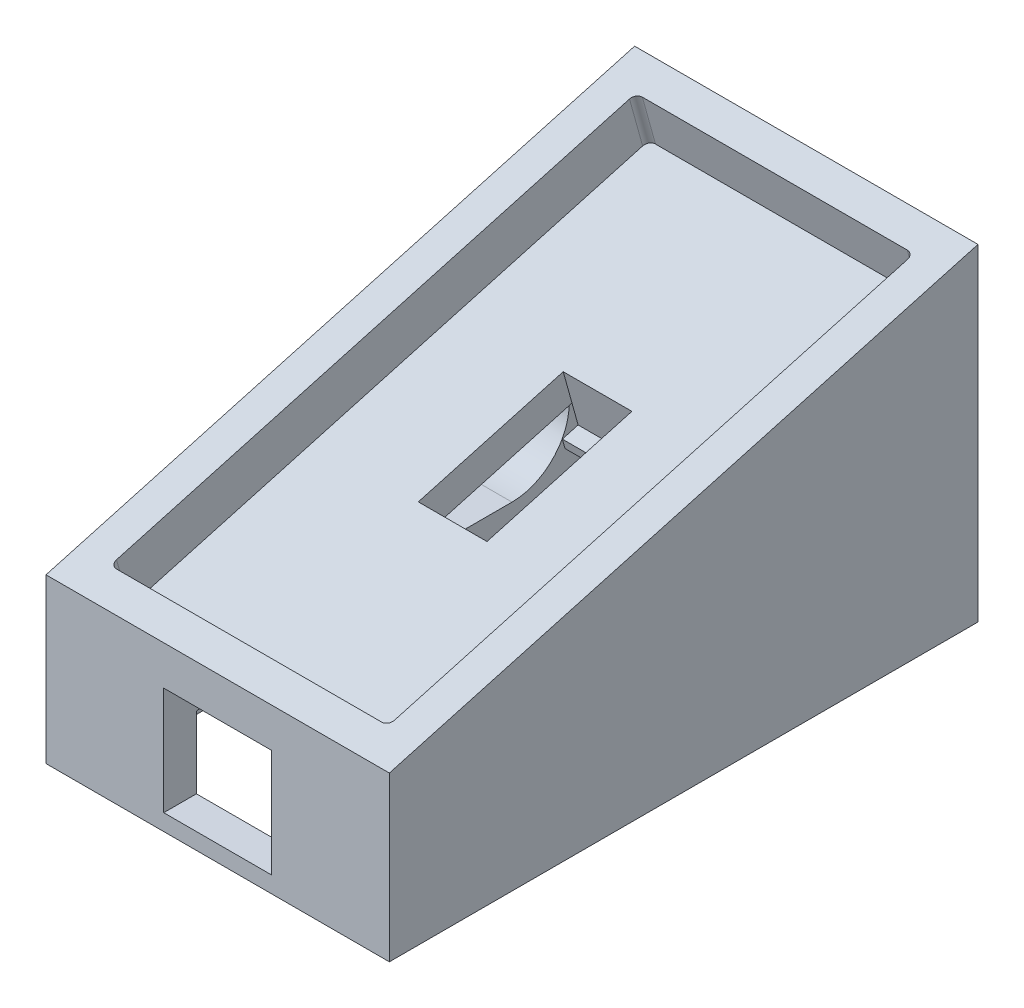
SolidWorks part; units mm, degrees
ref_plane "Front Plane" through (0, 0, 0) normal (0, 0, 1) x (1, 0, 0)
ref_plane "Top Plane" through (0, 0, 0) normal (0, 1, 0) x (1, 0, 0)
ref_plane "Right Plane" through (0, 0, 0) normal (1, 0, 0) x (0, 0, -1)
sketch "Sketch2" plane through (0, 0, 0) normal (0, 1, 0) x (1, 0, 0)
  line L0 (0, 0) -> (300, 0)
  line L1 (300, 0) -> (300, 180)
  line L2 (300, 180) -> (0, 180)
  line L3 (0, 180) -> (0, 0)
  line L4 (300, 0) -> (174.5704, 0)
  dimension "D1" = 180
  dimension "D2" = 300
extrude "Boss-Extrude1" add sketch "Sketch2" along normal blind 50 contours L3 L0 L1 L2
sketch "Sketch3" plane through (0, 50, 0) normal (0, 1, 0) x (1, 0, 0)
  line L0 (0, 0) -> (5, 0)
  line L1 (0, 0) -> (300, 0) construction
  line L2 (90, 12) -> (90, 73)
  line L5 (0, 180) -> (0, 0) construction
  line L13 (12, 10) -> (78, 10)
  line L14 (10, 12) -> (10, 73)
  line L15 (12, 75) -> (78, 75)
  line L16 (80, 12) -> (80, 73)
  line L22 (10, 10) -> (80, 10)
  line L26 (92, 10) -> (183, 10)
  line L27 (90, 10) -> (90, 75)
  line L28 (92, 75) -> (183, 75)
  line L29 (185, 12) -> (185, 73)
  line L30 (180, 70) -> (180, 75)
  line L32 (90, 10) -> (185, 10)
  line L34 (10, 75) -> (10, 10)
  line L35 (90, 10) -> (90, 75) construction
  line L37 (80, 10) -> (80, 75) construction
  arc A0 (90, 12) -> (92, 10) centre (92, 12) ccw
  arc A1 (185, 12) -> (183, 10) centre (183, 12) cw
  arc A2 (183, 75) -> (185, 73) centre (183, 73) cw
  arc A3 (80, 73) -> (78, 75) centre (78, 73) ccw
  arc A4 (12, 10) -> (10, 12) centre (12, 12) cw
  arc A5 (80, 12) -> (78, 10) centre (78, 12) cw
  arc A6 (10, 73) -> (12, 75) centre (12, 73) cw
  arc A7 (92, 75) -> (90, 73) centre (92, 73) ccw
  point P32 (80, 75)
  dimension "D7" = 2
  dimension "D4" = 2
  dimension "D1" = 10
  dimension "D3" = 65
  dimension "D5" = 70
  dimension "D8" = 95
  dimension "D9" = 65
  dimension "D2" = 10
  dimension "D11" = 10
extrude "Cut-Extrude1" cut sketch "Sketch3" against normal blind 15 contours L13 L16 L15 L14 | L26 L29 L28 L2
sketch "Sketch6" plane through (0, 50, 0) normal (0, 1, 0) x (1, 0, 0)
  line L2 (185, 12) -> (185, 73) construction
  line L4 (0, 180) -> (185, 180)
  line L14 (0, 180) -> (0, 95)
  line L15 (0, 95) -> (185, 95)
  line L16 (185, 168) -> (185, 107)
  line L17 (80, 107) -> (80, 168)
  line L23 (90, 107) -> (90, 168)
  line L25 (12, 170) -> (78, 170)
  line L26 (10, 168) -> (10, 107)
  line L27 (12, 105) -> (78, 105)
  line L32 (195, 180) -> (195, 95)
  line L34 (185, 180) -> (195, 180)
  line L35 (195, 95) -> (185, 95)
  line L37 (92, 105) -> (183, 105)
  line L44 (0, 105) -> (185, 105) construction
  line L45 (92, 170) -> (183, 170)
  line L46 (0, 170) -> (185, 170) construction
  line L47 (10, 180) -> (10, 95) construction
  line L48 (185, 180) -> (185, 95) construction
  arc A0 (185, 107) -> (183, 105) centre (183, 107) cw
  arc A1 (185, 168) -> (183, 170) centre (183, 168) ccw
  arc A2 (90, 168) -> (92, 170) centre (92, 168) cw
  arc A3 (90, 107) -> (92, 105) centre (92, 107) ccw
  arc A4 (12, 105) -> (10, 107) centre (12, 107) cw
  arc A5 (78, 105) -> (80, 107) centre (78, 107) ccw
  arc A6 (80, 168) -> (78, 170) centre (78, 168) ccw
  arc A7 (10, 168) -> (12, 170) centre (12, 168) cw
  point P30 (90, 105)
  point P33 (10, 105)
  point P38 (80, 170)
  point P41 (10, 170)
  dimension "D3" = 10
  dimension "D8" = 2
  dimension "D2" = 10
  dimension "D4" = 10
  dimension "D5" = 70
  dimension "D7" = 65
  dimension "D1" = 10
extrude "Boss-Extrude4" add sketch "Sketch6" along normal blind 50
sketch "Sketch10" plane through (0, 50, 0) normal (0, 1, 0) x (1, 0, 0)
  line L1 (195, 180) -> (300, 180)
  line L2 (195, 180) -> (195, 0)
  line L3 (195, 0) -> (300, 0)
  line L4 (300, 180) -> (300, 0)
extrude "Boss-Extrude7" add sketch "Sketch10" along normal blind 50
sketch "Sketch11" plane through (300, 0, 0) normal (1, 0, 0) x (0, 0, -1)
  line L1 (0, 100) -> (180, 100)
  line L2 (0, 100) -> (0, 50)
  line L5 (0, 50) -> (180, 100)
extrude "Cut-Extrude3" cut sketch "Sketch11" against normal blind 105
sketch "Sketch13" plane through (0, 46.4183, 12.894) normal (0, 0.9635, 0.2676) x (1, 0, 0)
  line L7 (288, 190.1976) -> (207, 190.1976)
  line L10 (205, 188.1976) -> (205, 25.3822)
  line L14 (290, 25.3822) -> (290, 188.1976)
  line L15 (300, 13.3822) -> (300, 200.1976) construction
  line L16 (207, 23.3822) -> (288, 23.3822)
  line L17 (195, 13.3822) -> (300, 13.3822) construction
  line L18 (300, 200.1976) -> (195, 200.1976) construction
  arc A0 (290, 188.1976) -> (288, 190.1976) centre (288, 188.1976) ccw
  arc A1 (288, 23.3822) -> (290, 25.3822) centre (288, 25.3822) ccw
  arc A2 (205, 25.3822) -> (207, 23.3822) centre (207, 25.3822) ccw
  arc A3 (205, 188.1976) -> (207, 190.1976) centre (207, 188.1976) cw
  point P12 (290, 190.1976)
  point P19 (205, 190.1976)
  dimension "D5" = 2
  dimension "D4" = 85
  dimension "D3" = 10
  dimension "D1" = 10
  dimension "D2" = 10
extrude "Cut-Extrude4" cut sketch "Sketch13" against normal blind 15
sketch "Sketch14" plane through (0, 50, 0) normal (0, 1, 0) x (1, 0, 0)
  line L1 (10, 105) -> (80, 105)
  line L2 (10, 105) -> (10, 170)
  line L3 (10, 170) -> (80, 170)
  line L4 (80, 105) -> (80, 170)
  line L5 (90, 170) -> (185, 170)
  line L6 (90, 170) -> (90, 105)
  line L7 (90, 105) -> (185, 105)
  line L8 (185, 170) -> (185, 105)
extrude "Boss-Extrude8" add sketch "Sketch14" along normal blind 35
sketch "Sketch15" plane through (0, 0, 0) normal (-1, 0, 0) x (0, 0, 1)
  line L6 (-180, 0) -> (0, 0)
  line L7 (0, 0) -> (0, 50)
  line L8 (0, 50) -> (-95, 50)
  line L9 (-95, 50) -> (-95, 100)
  line L10 (-95, 100) -> (-180, 100)
  line L11 (-180, 100) -> (-180, 0)
  line L12 (-180, 0) -> (0, 0)
  line L13 (0, 0) -> (0, 50)
  line L14 (0, 50) -> (-95, 50)
  line L15 (-95, 50) -> (-95, 100)
  line L16 (-95, 100) -> (-180, 100)
  line L17 (-180, 100) -> (-180, 0)
  dimension "D1" = 0
extrude "Cut-Extrude5" cut sketch "Sketch15" against normal up to surface (195 mm away) up to face at (195, 58.7963, -63.3333)
shell "Shell1" thickness 10
sketch "Sketch16" plane through (0, 31.9656, 8.8793) normal (0, 0.9635, 0.2676) x (1, 0, 0)
  line L0 (237, 83.7822) -> (258, 83.7822)
  line L1 (258, 83.7822) -> (258, 129.7822)
  line L2 (258, 129.7822) -> (237, 129.7822)
  line L3 (237, 129.7822) -> (237, 83.7822)
  line L6 (288, 190.1976) -> (207, 190.1976) construction
  dimension "D1" = 46
  dimension "D2" = 46
  dimension "D3" = 21
  dimension "D4" = 60.4154
extrude "Cut-Extrude7" cut sketch "Sketch16" against normal blind 10 contours L2 L3 L0 L1
sketch "Sketch17" plane through (195, 0, 0) normal (-1, 0, 0) x (0, 0, 1)
  line L0 (-150, 25.5) -> (-180, 25.5)
  line L1 (-180, 100) -> (-180, 0) construction
  line L2 (-132.5, 8) -> (-132.5, 0)
  line L3 (-180, 0) -> (0, 0) construction
  line L4 (-30, 25.5) -> (0, 25.5)
  line L5 (0, 0) -> (0, 50) construction
  line L6 (-47.5, 8) -> (-47.5, 0)
  circle A0 centre (-132.5, 25.5) radius 17.5
  circle A1 centre (-47.5, 25.5) radius 17.5
  dimension "D1" = 35
  dimension "D4" = 35
  dimension "D2" = 30
  dimension "D3" = 8
  dimension "D5" = 8
  dimension "D6" = 30
sketch "Sketch20" plane through (0, 0, 0) normal (0, 0, 1) x (1, 0, 0)
  line L0 (195, 25) -> (231, 25)
  line L1 (195, 0) -> (195, 50) construction
  line L3 (245, 38) -> (264, 38)
  line L5 (264, 38) -> (231, 38)
  line L6 (264, 38) -> (264, 5)
  line L7 (264, 5) -> (231, 5)
  line L8 (231, 38) -> (231, 5)
  line L9 (231, 38) -> (237, 38)
  line L10 (231, 38) -> (231, 34)
  line L15 (195, 0) -> (300, 0) construction
  dimension "D1" = 5
  dimension "D2" = 33
  dimension "D3" = 33
extrude "Cut-Extrude15" cut sketch "Sketch17" against normal blind 10 contours A0 | A1
extrude "Cut-Extrude16" cut sketch "Sketch20" against normal blind 10 contours L5 L8 L7 L6 L3
sketch "Sketch22" plane through (264, 0, 0) normal (-1, 0, 0) x (0, 0, 1)
  line L0 (-10, 38) -> (-50.0925, 38)
  line L1 (-10, 26.8312) -> (-10, 38)
  line L3 (-10, 26.8312) -> (-50.0925, 26.8312)
  line L4 (-50.0925, 26.8312) -> (-50.0925, 38)
extrude "Cut-Extrude17" cut sketch "Sketch22" along normal blind 33
sketch "Sketch23" plane through (0, 34.7354, -125.0475) normal (0, -0.2676, 0.9635) x (1, 0, 0)
  line L0 (237, 23.1759) -> (237, 13.1759)
  line L1 (237, 13.1759) -> (258, 13.1759)
  line L2 (258, 23.1759) -> (258, 13.1759)
  line L4 (237, 23.1759) -> (258, 23.1759)
  dimension "D1" = 10
extrude "Boss-Extrude9" add sketch "Sketch23" against normal blind 3
sketch "Sketch24" plane through (0, 34.7354, -125.0475) normal (0, -0.2676, 0.9635) x (1, 0, 0)
  line L1 (237, 13.1759) -> (258, 13.1759)
  line L2 (237, 13.1759) -> (237, 16.1759)
  line L3 (237, 16.1759) -> (258, 16.1759)
  line L4 (258, 13.1759) -> (258, 16.1759)
  dimension "D1" = 3
extrude "Boss-Extrude10" add sketch "Sketch24" along normal blind 5
sketch "Sketch25" plane through (0, 31.9656, 8.8793) normal (0, 0.9635, 0.2676) x (1, 0, 0)
  line L0 (237, 106.7822) -> (258, 106.7822)
  line L1 (237, 129.7822) -> (237, 83.7822) construction
  line L2 (258, 83.7822) -> (258, 129.7822) construction
ref_plane "Plane1" through (0, 28.5796, -102.8866) normal (0, -0.2676, 0.9635) x (1, 0, 0)
mirror "Mirror1" about plane through (0, 28.5796, -102.8866) normal (0, -0.2676, 0.9635) of "Boss-Extrude10", "Boss-Extrude9"
sketch "Sketch26" plane through (195, 0, 0) normal (-1, 0, 0) x (0, 0, 1)
  line L0 (-132.5, 43) -> (-47.5, 43)
  line L1 (-132.5, 8) -> (-47.5, 8)
  circle A0 centre (-132.5, 25.5) radius 17.5 construction
  circle A1 centre (-47.5, 25.5) radius 17.5 construction
  arc A3 (-31.6111, 32.8343) -> (-57.3299, 39.9784) centre (-47.5, 25.5) ccw construction
  arc A4 (-47.5, 43) -> (-47.5, 8) centre (-47.5, 25.5) ccw
  arc A5 (-132.5, 8) -> (-132.5, 43) centre (-132.5, 25.5) ccw
extrude "Cut-Extrude18" cut sketch "Sketch26" against normal blind 10 contours A4 L1 A5 L0
sketch "Sketch27" plane through (0, 0, -180) normal (0, 0, -1) x (-1, 0, 0)
  line L0 (-247.5, 0) -> (-247.5, 30)
  line L1 (-300, 0) -> (-195, 0) construction
  line L3 (-260.5, 30) -> (-234.5, 30)
  line L4 (-260.5, 30) -> (-260.5, 60)
  line L5 (-260.5, 60) -> (-234.5, 60)
  line L6 (-234.5, 30) -> (-234.5, 60)
  dimension "D1" = 26
  dimension "D2" = 30
  dimension "D3" = 30
extrude "Cut-Extrude19" cut sketch "Sketch27" against normal blind 10 contours L3 L6 L5 L4
